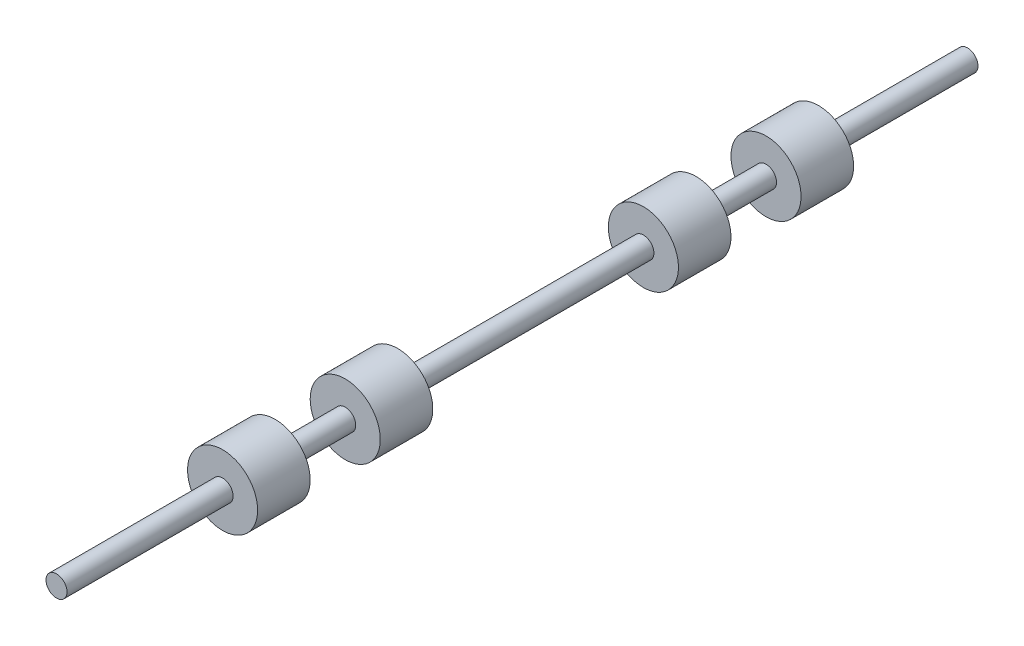
SolidWorks part; units mm, degrees
ref_plane "Front Plane" through (0, 0, 0) normal (0, 0, 1) x (1, 0, 0)
ref_plane "Top Plane" through (0, 0, 0) normal (0, 1, 0) x (1, 0, 0)
ref_plane "Right Plane" through (0, 0, 0) normal (1, 0, 0) x (0, 0, -1)
sketch "Sketch2" plane through (0, 0, 0) normal (0, 0, 1) x (1, 0, 0)
  circle A0 centre (0, 0) radius 0.3
  dimension "D1" = 0.6
extrude "Boss-Extrude1" add sketch "Sketch2" along normal blind 26
sketch "Sketch3" plane through (0, 0, 0) normal (0, 1, 0) x (1, 0, 0)
  line L0 (0, 1.2496) -> (0, -27.4238) construction
  line L1 (0, -18.76) -> (5.8783, -18.76) construction
  line L2 (0, -4.25) -> (1, -4.25)
  line L3 (0, -4.25) -> (0, -5.75)
  line L4 (0, -5.75) -> (1, -5.75)
  line L5 (1, -4.25) -> (1, -5.75)
  line L6 (0, -7.75) -> (1, -7.75)
  line L7 (0, -7.75) -> (0, -9.25)
  line L8 (0, -9.25) -> (1, -9.25)
  line L9 (1, -7.75) -> (1, -9.25)
  line L10 (0, -16.26) -> (1, -16.26)
  line L11 (0, -16.26) -> (0, -17.76)
  line L12 (0, -17.76) -> (1, -17.76)
  line L13 (1, -16.26) -> (1, -17.76)
  line L14 (0, -19.76) -> (1, -19.76)
  line L15 (0, -19.76) -> (0, -21.26)
  line L16 (0, -21.26) -> (1, -21.26)
  line L17 (1, -19.76) -> (1, -21.26)
  line L18 (0, -6.75) -> (9.1458, -6.75) construction
  line L20 (-0.3, -26) -> (0.3, -26) construction
  dimension "D1" = 1.5
  dimension "D2" = 1.5
  dimension "D3" = 1.5
  dimension "D4" = 1.5
  dimension "D5" = 1
  dimension "D6" = 1
  dimension "D7" = 1
  dimension "D8" = 1
  dimension "D9" = 2
  dimension "D10" = 2
  dimension "D11" = 7.24
  dimension "D12" = 12.01
revolve "Revolve1" add sketch "Sketch3" angle 360 about L0
